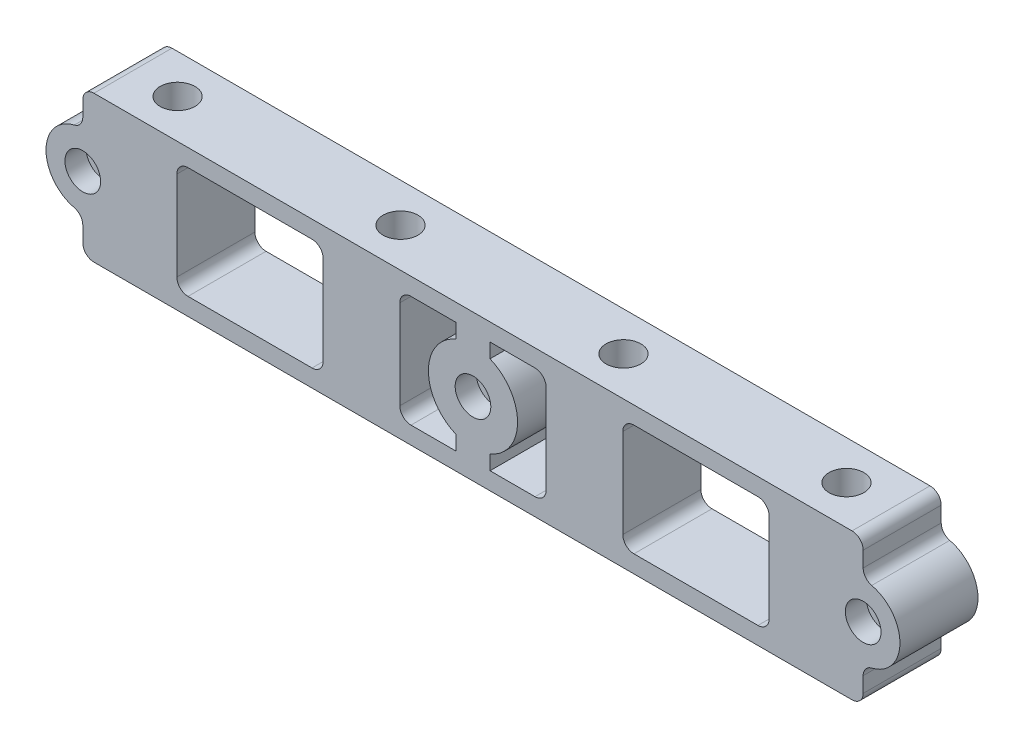
SolidWorks part; units mm, degrees
material "6061-T6 (SS)"
ref_plane "X-Y Datum" through (0, 0, 0) normal (0, 0, 1) x (1, 0, 0)
ref_plane "X-Z Datum" through (0, 0, 0) normal (0, 1, 0) x (1, 0, 0)
ref_plane "Y-Z Datum" through (0, 0, 0) normal (1, 0, 0) x (0, 0, -1)
other "Graphic1"
other "Graphic (Closed) -1"
other "Graphic2"
other "Graphic (Closed) -2"
other "Graphic3"
other "Graphic (Closed) -3"
sketch "Sketch1" plane through (0, 0, 0) normal (0, 0, 1) x (1, 0, 0)
  line L1 (8.7312, 16.6687) -> (-186.5312, 16.6687)
  line L5 (-8.7312, 0) -> (0, 0) construction
  line L7 (-186.5312, -16.6687) -> (-186.5312, 16.6687)
  line L8 (-8.7312, 0) -> (-16.6687, 0) construction
  line L9 (-8.7312, 0) -> (-8.7312, 16.6687) construction
  line L10 (-8.7312, 16.6687) -> (-16.6688, 16.6687) construction
  line L11 (-16.6687, 0) -> (-16.6688, 16.6687) construction
  line L12 (-67.4688, 0) -> (-59.5313, 0) construction
  line L13 (-67.4688, 0) -> (-67.4688, 16.6687) construction
  line L14 (-67.4688, 16.6687) -> (-59.5313, 16.6687) construction
  line L15 (-59.5313, 0) -> (-59.5313, 16.6687) construction
  line L17 (-186.5312, -16.6687) -> (8.7312, -16.6687)
  line L19 (8.7312, -16.6687) -> (8.7312, 16.6687)
  line L20 (-110.3313, 16.6687) -> (-118.2687, 16.6687) construction
  line L21 (-110.3313, 16.6687) -> (-110.3313, 0) construction
  line L22 (-110.3313, 0) -> (-118.2687, 0) construction
  line L23 (-118.2687, 16.6687) -> (-118.2687, 0) construction
  line L24 (-161.1313, 16.6687) -> (-169.0688, 16.6687) construction
  line L25 (-161.1313, 16.6687) -> (-161.1313, 0) construction
  line L26 (-161.1313, 0) -> (-169.0688, 0) construction
  line L27 (-169.0688, 16.6687) -> (-169.0688, 0) construction
  line L28 (0, 0) -> (8.7312, 0) construction
  line L29 (-177.8, 0) -> (-186.5312, 0) construction
  circle A0 centre (0, 0) radius 2.4892
  circle A4 centre (-177.8, 0) radius 2.4892
  circle A6 centre (-88.9, 0) radius 2.4892
  point P1 (-186.5312, 0)
  point P22 (-12.7, 0)
  point P23 (-63.5, 0)
  point P31 (-114.3, 0)
  point P32 (-165.1, 0)
  point P38 (-88.9, -16.6687)
  dimension "D2" = 4.9784
  dimension "D3" = 12.7
  dimension "D1" = 50.8
  dimension "D4" = 12.7
  dimension "D6" = 7.9375
  dimension "D7" = 7.9375
  dimension "D8" = 33.3375
  dimension "D11" = 50.8
  dimension "D12" = 50.8
extrude "Boss-Extrude1" add sketch "Sketch1" against normal blind 17.78
ref_plane "Plane1" through (0, 0, 0) normal (0, -1, 0) x (-1, 0, 0)
sketch "Sketch2" plane through (0, 16.6687, 0) normal (0, 1, 0) x (1, 0, 0)
  line L0 (-186.5312, 0) -> (8.7313, 0) construction
  line L4 (0, 0) -> (0, 17.78) construction
  line L5 (8.7313, 17.78) -> (-186.5312, 17.78) construction
  circle A0 centre (-12.7, 8.89) radius 3.9688
  circle A2 centre (-63.5, 8.89) radius 3.9688
  circle A3 centre (-114.3, 8.89) radius 3.9687
  circle A4 centre (-165.1, 8.89) radius 3.9688
  dimension "D2" = 7.9375
  dimension "D1" = 4
  dimension "D3" = 8.89
  dimension "D4" = 12.7
  dimension "D5" = 50.8
extrude "Cut-Extrude1" cut sketch "Sketch2" against normal up to surface (33.3375 mm away) up to face at (-88.9, -16.6687, -8.89)
sketch "Sketch3" plane through (0, 0, 0) normal (0, 0, 1) x (1, 0, 0)
  circle A0 centre (0, 0) radius 4.064
  circle A1 centre (-88.9, 0) radius 4.064
  circle A2 centre (-177.8, 0) radius 4.064
  circle A3 centre (-177.8, 0) radius 2.4892 construction
  dimension "D1" = 8.128
extrude "Cut-Extrude2" cut sketch "Sketch3" against normal blind 4.826
ref_point "Point1"
ref_point "Point2"
ref_point "Point3"
ref_point "Point4"
sketch "Sketch5" plane through (0, 0, 0) normal (0, 0, 1) x (1, 0, 0)
  line L0 (0, -16.6687) -> (8.7312, -16.6687)
  line L1 (0, -10.6225) -> (0, -16.6687)
  line L2 (-186.5312, -16.6687) -> (8.7312, -16.6687) construction
  line L3 (0, 10.6225) -> (0, 16.6687)
  line L4 (8.7312, 16.6687) -> (-186.5312, 16.6687) construction
  line L5 (8.7312, -16.6687) -> (8.7312, 16.6687)
  line L6 (8.7312, 16.6687) -> (0, 16.6687)
  line L7 (-88.9, -16.6687) -> (-88.9, 16.6687) construction
  line L8 (0, 0) -> (-21.4313, 0) construction
  line L9 (-23.9713, -12.7) -> (-52.2288, -12.7)
  line L10 (-21.4313, -10.16) -> (-21.4313, 10.16)
  line L11 (-23.9713, 12.7) -> (-52.2288, 12.7)
  line L12 (-54.7688, -10.16) -> (-54.7688, 10.16)
  line L13 (-85.0119, -9.3866) -> (-85.0119, -12.7)
  line L14 (-85.0119, -12.7) -> (-74.7712, -12.7)
  line L15 (-72.2313, -10.16) -> (-72.2313, 10.16)
  line L16 (-74.7712, 12.7) -> (-85.0119, 12.7)
  line L17 (-85.0119, 12.7) -> (-85.0119, 9.3866)
  line L18 (-88.9, 0) -> (-85.0119, -9.3866) construction
  line L19 (-88.9, 0) -> (-85.0119, 9.3866) construction
  line L20 (-103.0287, 12.7) -> (-92.7881, 12.7)
  line L21 (-105.5687, -10.16) -> (-105.5687, 10.16)
  line L22 (-92.7881, -12.7) -> (-103.0287, -12.7)
  line L23 (-92.7881, -9.3866) -> (-92.7881, -12.7)
  line L24 (-92.7881, 12.7) -> (-92.7881, 9.3866)
  line L25 (-153.8287, 12.7) -> (-125.5712, 12.7)
  line L26 (-123.0312, -10.16) -> (-123.0312, 10.16)
  line L27 (-153.8287, -12.7) -> (-125.5712, -12.7)
  line L28 (-156.3687, -10.16) -> (-156.3687, 10.16)
  line L29 (-186.5312, -16.6687) -> (-186.5312, 16.6687)
  line L30 (-177.8, -16.6687) -> (-186.5312, -16.6687)
  line L31 (-177.8, -10.6225) -> (-177.8, -16.6687)
  line L32 (-177.8, 10.6225) -> (-177.8, 16.6687)
  line L33 (-186.5312, 16.6687) -> (-177.8, 16.6687)
  arc A0 (1.9493, 8.1522) -> (1.9493, -8.1522) centre (0, 0) cw
  arc A1 (-85.0119, -9.3866) -> (-85.0119, 9.3866) centre (-88.9, 0) ccw
  arc A2 (0, -10.6225) -> (1.9493, -8.1522) centre (2.54, -10.6225) cw
  arc A3 (-23.9713, 12.7) -> (-21.4313, 10.16) centre (-23.9712, 10.16) cw
  arc A4 (-54.7688, 10.16) -> (-52.2288, 12.7) centre (-52.2288, 10.16) cw
  arc A5 (-54.7688, -10.16) -> (-52.2288, -12.7) centre (-52.2288, -10.16) ccw
  arc A6 (0, 10.6225) -> (1.9493, 8.1522) centre (2.54, 10.6225) ccw
  arc A7 (-23.9713, -12.7) -> (-21.4313, -10.16) centre (-23.9712, -10.16) ccw
  arc A8 (-92.7881, -9.3866) -> (-92.7881, 9.3866) centre (-88.9, 0) cw
  arc A9 (-123.0312, 10.16) -> (-125.5712, 12.7) centre (-125.5712, 10.16) ccw
  arc A10 (-123.0312, -10.16) -> (-125.5712, -12.7) centre (-125.5712, -10.16) cw
  arc A11 (-153.8287, 12.7) -> (-156.3687, 10.16) centre (-153.8287, 10.16) ccw
  arc A12 (-153.8287, -12.7) -> (-156.3687, -10.16) centre (-153.8287, -10.16) cw
  arc A13 (-177.8, -10.6225) -> (-179.7493, -8.1522) centre (-180.34, -10.6225) ccw
  arc A14 (-179.7493, 8.1522) -> (-179.7493, -8.1522) centre (-177.8, 0) ccw
  arc A15 (-177.8, 10.6225) -> (-179.7493, 8.1522) centre (-180.34, 10.6225) cw
  arc A16 (-105.5687, 10.16) -> (-103.0287, 12.7) centre (-103.0287, 10.16) cw
  arc A17 (-105.5687, -10.16) -> (-103.0287, -12.7) centre (-103.0287, -10.16) ccw
  arc A18 (-74.7712, 12.7) -> (-72.2313, 10.16) centre (-74.7712, 10.16) cw
  arc A19 (-74.7712, -12.7) -> (-72.2313, -10.16) centre (-74.7712, -10.16) ccw
  point P26 (0, -8.382)
  point P35 (-54.7688, 12.7)
  point P38 (-54.7688, -12.7)
  point P41 (0, 8.382)
  point P44 (-21.4313, -12.7)
  point P76 (-105.5687, 12.7)
  point P79 (-105.5687, -12.7)
  point P82 (-72.2313, 12.7)
  point P85 (-72.2313, -12.7)
  point P86 (-38.1, -12.7)
  dimension "D1" = 8.382
  dimension "D5" = 10.16
  dimension "D7" = 2.54
  dimension "D8" = 2.54
  dimension "D10" = 2.54
  dimension "D2" = 46.8312
  dimension "D3" = 33.3375
  dimension "D4" = 25.4
  dimension "D6" = 16.6687
  dimension "D9" = 135
extrude "Cut-Extrude3" cut sketch "Sketch5" against normal up to surface (17.78 mm away) up to face at (-86.4108, 0, -17.78)
fillet "Fillet1" radius 2.54 4 edges at (0, -16.6687, -8.89) (0, 16.6688, -8.89) (-177.8, -16.6687, -8.89) (-177.8, 16.6688, -8.89)
